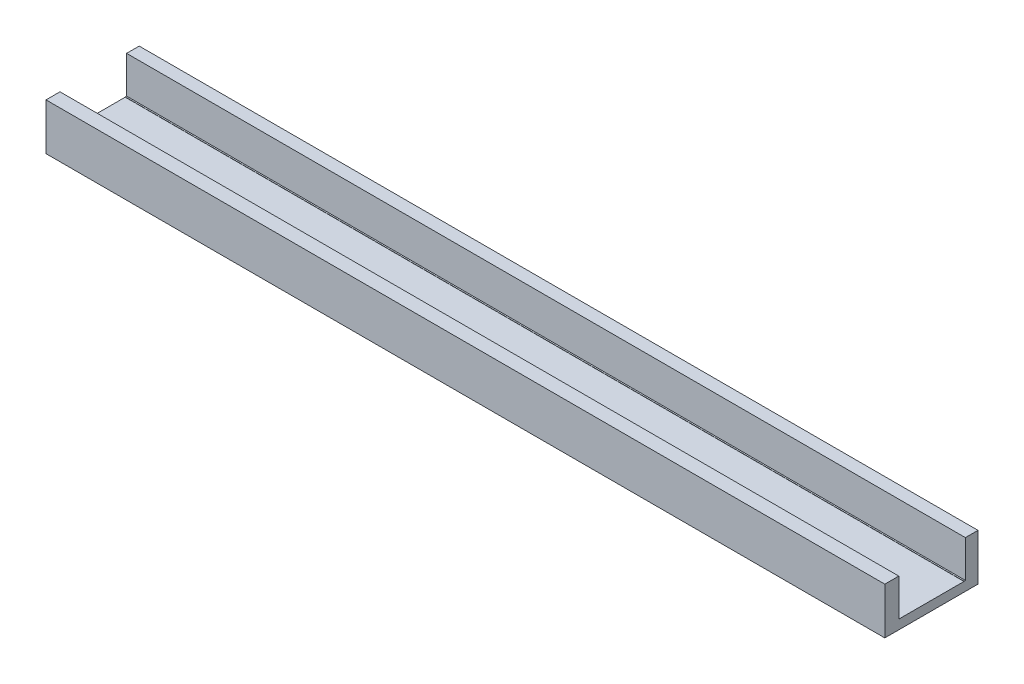
SolidWorks part; units mm, degrees
ref_plane "Plan de face" through (0, 0, 0) normal (0, 0, 1) x (1, 0, 0)
ref_plane "Plan de dessus" through (0, 0, 0) normal (0, 1, 0) x (1, 0, 0)
ref_plane "Plan de droite" through (0, 0, 0) normal (1, 0, 0) x (0, 0, -1)
sketch "Esquisse1" plane through (0, 0, 0) normal (0, 0, 1) x (1, 0, 0)
  line L0 (900, 0) -> (-900, 0)
  line L1 (-900, 0) -> (-900, -100)
  line L2 (-900, -100) -> (900, -100)
  line L3 (900, -100) -> (900, 0)
  point P4 (0, 0)
  dimension "D1" = 1800
  dimension "D2" = 100
extrude "Boss.-Extru.1" add sketch "Esquisse1" along normal blind 200 contours L3 L0 L1 L2
sketch "Esquisse2" plane through (0, 0, 0) normal (0, 1, 0) x (1, 0, 0)
  line L0 (-900, -30) -> (900, -30)
  line L1 (-900, -200) -> (-900, 0) construction
  line L2 (900, -200) -> (900, 0) construction
  line L3 (-900, -170) -> (900, -170)
  line L4 (900, 0) -> (-900, 0) construction
  line L5 (900, -200) -> (-900, -200) construction
  line L6 (-900, -30) -> (-900, -170)
  line L7 (900, -30) -> (900, -170)
  dimension "D1" = 30
  dimension "D2" = 30
extrude "Enlèv. mat.-Extru.1" cut sketch "Esquisse2" against normal blind 80
sketch "Esquisse4" plane through (0, 0, 0) normal (0, 1, 0) x (1, 0, 0)
  line L0 (-900, -23.5228) -> (900, -23.5228)
  line L1 (-900, -30) -> (-900, 0) construction
  line L2 (900, -30) -> (900, 0) construction
  line L3 (900, -27.0585) -> (-900, -27.0585)
  line L4 (900, -27.0585) -> (900, -30)
  line L5 (900, -23.5228) -> (900, -27.0585)
  line L6 (900, -23.5228) -> (900, -27.0585)
  line L7 (-900, -23.5228) -> (-900, -27.0585)
  line L8 (-900, -27.0585) -> (-900, -30)
  line M1 (-900, 0) -> (-900, -30)
  line M2 (-900, -30) -> (900, -30)
  line M3 (900, -30) -> (900, 0)
extrude "Enlèv. mat.-Extru.2" cut sketch "Esquisse4" against normal blind 79.5 contours L3 M3 M1 M2
